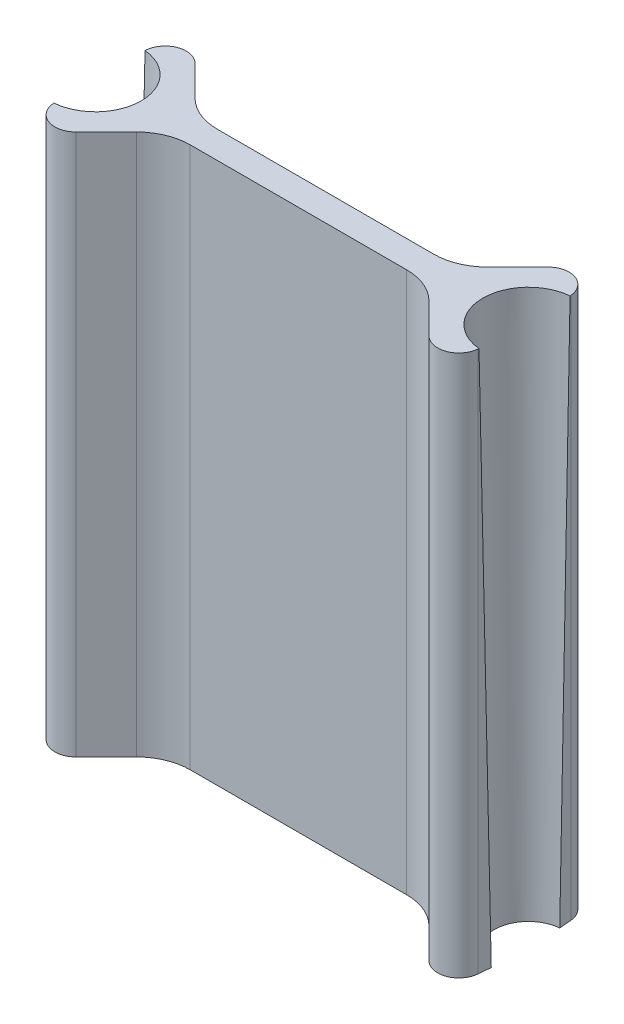
SolidWorks part; units mm, degrees
ref_plane "Front Plane" through (0, 0, 0) normal (0, 0, 1) x (1, 0, 0)
ref_plane "Top Plane" through (0, 0, 0) normal (0, 1, 0) x (1, 0, 0)
ref_plane "Right Plane" through (0, 0, 0) normal (1, 0, 0) x (0, 0, -1)
sketch "Sketch2" plane through (0, 0, 0) normal (0, 1, 0) x (1, 0, 0)
  line L0 (0, 0) -> (4, 0) construction
  line L1 (0, 0) -> (0.0553, 0.6326) construction
  line L2 (0.0553, 0.6326) -> (0.0751, 0.8586)
  line L3 (0.7385, 1.1) -> (1.2975, 0.541)
  line L4 (2, 0.25) -> (6, 0.25)
  line L5 (4, 0.25) -> (4, 0) construction
  line L6 (2, -0.25) -> (6, -0.25)
  line L7 (0.7385, -1.1) -> (1.2975, -0.541)
  line L8 (0.0553, -0.6326) -> (0.0751, -0.8586)
  line L9 (0.0553, 0.6326) -> (0.0553, -0.6326)
  line L10 (7.2615, -1.1) -> (6.7025, -0.541)
  line L11 (7.9447, -0.6326) -> (7.9249, -0.8586)
  line L12 (7.2615, 1.1) -> (6.7025, 0.541)
  line L13 (7.9447, 0.6326) -> (7.9249, 0.8586)
  line L14 (7.9447, 0.6326) -> (7.9447, -0.6326)
  line L15 (0, 0) -> (0.9192, -0.9192) construction
  circle A0 centre (0, 0) radius 0.635 construction
  circle A1 centre (8, 0) radius 0.635 construction
  arc A2 (0.0751, 0.8586) -> (0.7385, 1.1) centre (0.4631, 0.8246) cw
  arc A3 (1.2975, 0.541) -> (2, 0.25) centre (2, 1.2435) ccw
  arc A4 (1.2975, -0.541) -> (2, -0.25) centre (2, -1.2435) cw
  arc A5 (0.0751, -0.8586) -> (0.7385, -1.1) centre (0.4631, -0.8246) ccw
  arc A6 (6.7025, -0.541) -> (6, -0.25) centre (6, -1.2435) ccw
  arc A7 (6.7025, 0.541) -> (6, 0.25) centre (6, 1.2435) cw
  arc A8 (7.9249, -0.8586) -> (7.2615, -1.1) centre (7.5369, -0.8246) cw
  arc A10 (7.9249, 0.8586) -> (7.2615, 1.1) centre (7.5369, 0.8246) ccw
  point P27 (4, -0.25)
  dimension "D1" = 1.27
  dimension "D7" = 1.1
  dimension "D5" = 1.3
  dimension "D2" = 4
  dimension "D3" = 95
  dimension "D4" = 0.25
  dimension "D6" = 135
  dimension "D8" = 2
  dimension "D9" = 0.8246
extrude "Boss-Extrude2" add sketch "Sketch2" along normal blind 10
sketch "Sketch5" plane through (0, 0, 0) normal (0, -1, 0) x (1, 0, 0)
  circle A0 centre (0, 0) radius 0.635
  circle A1 centre (0, 0) radius 0.635 construction
  circle A2 centre (8, 0) radius 0.635
  circle A3 centre (8, 0) radius 0.635 construction
extrude "Cut-Extrude1" cut sketch "Sketch5" against normal up to next (10 mm away) draft 1.2 draft outward yes
